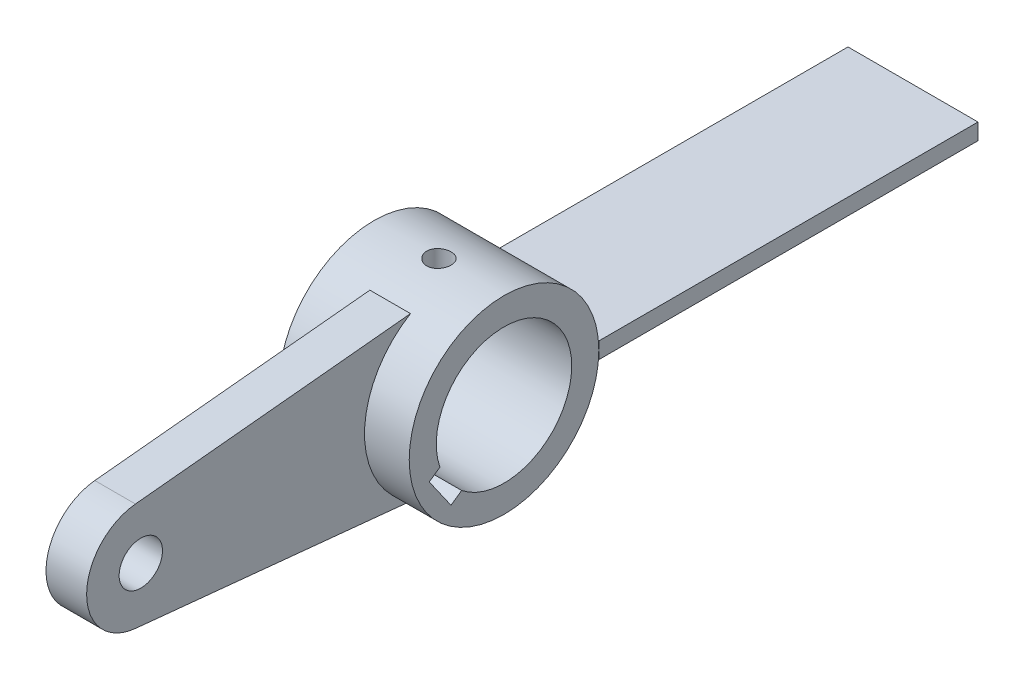
SolidWorks part; units mm, degrees
material "ASTM A36 Steel"
ref_plane "Front Plane" through (0, 0, 0) normal (0, 0, 1) x (1, 0, 0)
ref_plane "Top Plane" through (0, 0, 0) normal (0, 1, 0) x (1, 0, 0)
ref_plane "Right Plane" through (0, 0, 0) normal (1, 0, 0) x (0, 0, -1)
sketch "Sketch1" plane through (0, 0, 0) normal (1, 0, 0) x (0, 0, -1)
  circle A0 centre (0, 0) radius 25
  circle A1 centre (0, 0) radius 35
  dimension "D1" = 50
  dimension "D2" = 70
extrude "Boss-Extrude1" add sketch "Sketch1" along normal mid plane 48
sketch "Sketch2" plane through (0, 0, 0) normal (1, 0, 0) x (0, 0, -1)
  line L0 (-18.0278, 30) -> (-119.579, 19.9018)
  line L1 (-119.579, -19.9018) -> (-18.0278, -30)
  circle A0 centre (0, 0) radius 35 construction
  arc A1 (-119.579, 19.9018) -> (-119.579, -19.9018) centre (-117.6, 0) ccw
  circle A3 centre (0, 0) radius 35
  arc A4 (-18.0278, 30) -> (-18.0278, -30) centre (0, 0) ccw
  dimension "D2" = 20
  dimension "D1" = 117.6
  dimension "D3" = 60
  dimension "D4" = 0
extrude "Boss-Extrude2" add sketch "Sketch2" along normal mid plane 15
sketch "Sketch3" plane through (7.5, 0, 0) normal (1, 0, 0) x (0, 0, -1)
  circle A0 centre (-117.6, 0) radius 8
  dimension "D1" = 16
extrude "Cut-Extrude1" cut sketch "Sketch3" against normal blind 15
sketch "Sketch5" plane through (24, 0, 0) normal (1, 0, 0) x (0, 0, -1)
  line L0 (-2.5706, 6.7455) -> (-27.6066, -10.7849)
  line L1 (-2.5706, 6.7455) -> (5.4595, -4.7226)
  line L2 (-27.6066, -10.7849) -> (-19.5765, -22.2531)
  line L3 (5.4595, -4.7226) -> (-19.5765, -22.2531)
  line L4 (-3.7029, 6.1966) -> (-15.4149, -25.3144) construction
  line L5 (-25.3144, -15.4149) -> (6.1966, -3.7029) construction
  line L6 (0, 0) -> (-20.3647, -20.3647) construction
  line L7 (-9.5589, -9.5589) -> (-9.5589, 9.0644) construction
  point P1 (-9.5589, -9.5589)
  dimension "D1" = 28.8
  dimension "D2" = 14
  dimension "D3" = 135
extrude "Cut-Extrude2" cut sketch "Sketch5" against normal through all
ref_plane "Plane1" through (0, 0, -35) normal (0, 0, 1) x (1, 0, 0)
ref_plane "Plane2" through (0, 35, 0) normal (0, 1, 0) x (1, 0, 0)
sketch "Sketch6" plane through (0, 35, -70) normal (0, -1, 0) x (1, 0, 0)
  circle A0 centre (0, 70) radius 4.5
  dimension "D1" = 9
extrude "Cut-Extrude3" cut sketch "Sketch6" along normal blind 24
mirror "Mirror1" [suppressed] about plane through (0, 0, 0) normal (0, 0, 1)
sketch "Sketch7" plane through (0, 0, -35) normal (0, 0, 1) x (1, 0, 0)
  line L0 (24, -35) -> (24, 35) construction
  line L1 (-24, -3) -> (24, -3)
  line L2 (-24, -3) -> (-24, 3)
  line L3 (-24, 3) -> (24, 3)
  line L4 (24, -3) -> (24, 3)
  line L5 (-24, -3) -> (24, 3) construction
  line L6 (-24, 3) -> (24, -3) construction
  point P0 (0, 0)
  dimension "D1" = 6
extrude "Boss-Extrude3" add sketch "Sketch7" against normal blind 140 separate body
